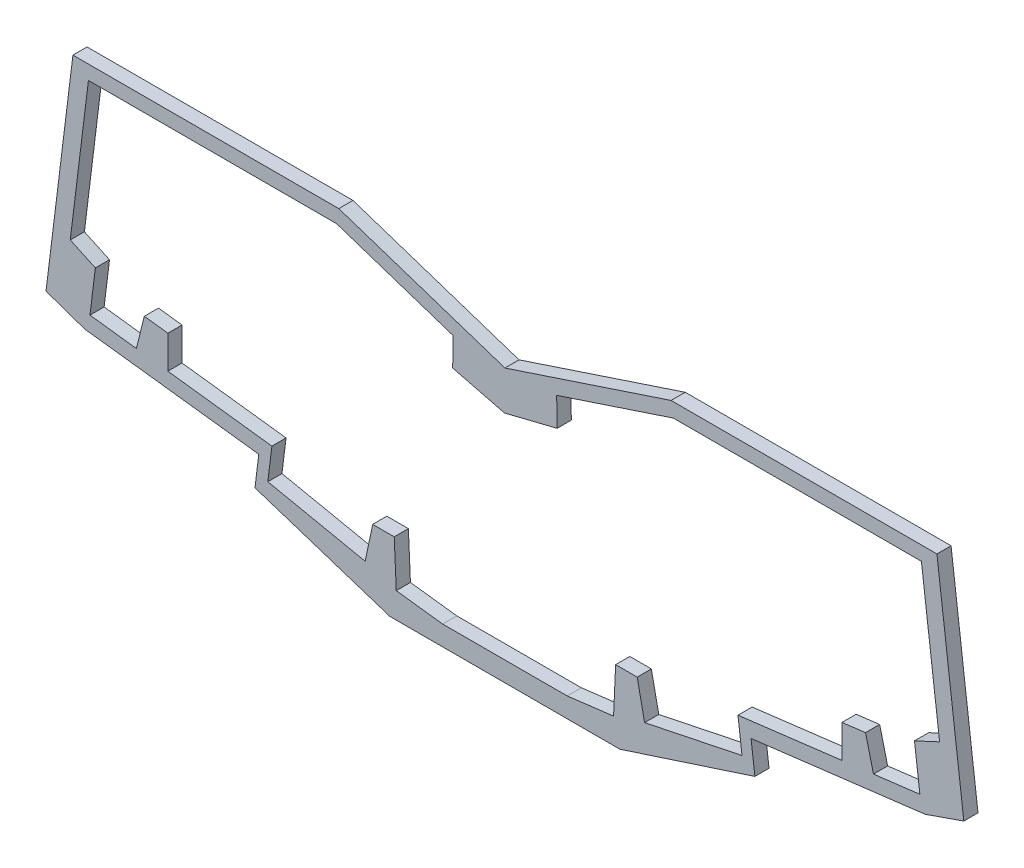
SolidWorks part; units mm, degrees
ref_plane "Спереди" through (0, 0, 0) normal (0, 0, 1) x (1, 0, 0)
ref_plane "Сверху" through (0, 0, 0) normal (0, 1, 0) x (1, 0, 0)
ref_plane "Справа" through (0, 0, 0) normal (1, 0, 0) x (0, 0, -1)
sketch "Контур" plane through (0, 0, 0) normal (0, 0, 1) x (1, 0, 0)
  line L0 (148.3547, -23.6716) -> (86.886, -31.2162)
  line L1 (162, -18.92) -> (148.3547, -23.6716)
  line L2 (-152.5, 58) -> (-58.64, 58)
  line L3 (86.886, -31.2162) -> (88.2371, -42.1562)
  line L4 (-10.9082, 11.6263) -> (-21.8482, 15.5133)
  line L5 (152.5, 58) -> (162, -18.92)
  line L6 (-88.2371, -42.1562) -> (-40.5971, -57.6623)
  line L7 (-58.64, 58) -> (0, 38.59)
  line L8 (-152.5, 58) -> (-162, -18.92)
  line L9 (58.64, 58) -> (0, 38.59)
  line L10 (-86.886, -31.2162) -> (-88.2371, -42.1562)
  line L11 (-40.5971, -57.6623) -> (40.5971, -57.6623)
  line L12 (-162, -18.92) -> (-148.3547, -23.6716)
  line L13 (0, 0) -> (0, -106.1018) construction
  line L14 (-148.3547, -23.6716) -> (-86.886, -31.2162)
  line L15 (88.2371, -42.1562) -> (40.5971, -57.6623)
  line L16 (152.5, 58) -> (58.64, 58)
  line L17 (-21.8482, 15.5133) -> (-18.6176, 3.8733)
  line L18 (21.8482, 15.5133) -> (18.6176, 3.8733)
  line L19 (10.9082, 11.6263) -> (21.8482, 15.5133)
  arc A0 (-18.6176, 3.8733) -> (18.6176, 3.8733) centre (0, -6.93) ccw
  arc A2 (10.9082, 11.6263) -> (-10.9082, 11.6263) centre (0, -6.93) ccw
  point P0 (0, 0)
  point P19 (0, -57.6623)
  dimension "D1" = 43.05
  dimension "D2" = 10.94
  dimension "D3" = 61.4687
  dimension "D6" = 47.64
  dimension "D7" = 50.1
  dimension "D8" = 11.64
  dimension "D9" = 12.08
  dimension "D10" = 11.61
  dimension "D11" = 45.52
sketch "Эскиз4" plane through (0, 0, 0) normal (0, 0, 1) x (1, 0, 0)
  line L0 (21.8482, 15.5133) -> (18.6176, 3.8733) construction
  line L1 (10.9082, 11.6263) -> (21.8482, 15.5133) construction
  line L2 (-10.9082, 11.6263) -> (-21.8482, 15.5133) construction
  line L3 (-21.8482, 15.5133) -> (-18.6176, 3.8733) construction
  line L4 (21.8482, 15.5133) -> (18.6176, 3.8733)
  line L5 (10.9082, 11.6263) -> (21.8482, 15.5133)
  line L6 (-10.9082, 11.6263) -> (-21.8482, 15.5133)
  line L7 (-21.8482, 15.5133) -> (-18.6176, 3.8733)
  line L12 (-21.8482, 15.5133) -> (-18.6176, 3.8733)
  line L13 (-21.8482, 15.5133) -> (-18.6176, 3.8733)
  line L14 (-10.9082, 11.6263) -> (-21.8482, 15.5133)
  line L15 (152.5, 58) -> (58.64, 58)
  line L16 (58.64, 58) -> (0, 38.59)
  line L17 (0, 38.59) -> (-58.64, 58)
  line L18 (-58.64, 58) -> (-152.5, 58)
  line L19 (-152.5, 58) -> (-162, -18.92)
  line L20 (-162, -18.92) -> (-148.3547, -23.6716)
  line L21 (-148.3547, -23.6716) -> (-86.886, -31.2162)
  line L22 (-86.886, -31.2162) -> (-88.2371, -42.1562)
  line L23 (-88.2371, -42.1562) -> (-40.5971, -57.6623)
  line L24 (-40.5971, -57.6623) -> (40.5971, -57.6623)
  line L25 (40.5971, -57.6623) -> (88.2371, -42.1562)
  line L26 (88.2371, -42.1562) -> (86.886, -31.2162)
  line L27 (86.886, -31.2162) -> (148.3547, -23.6716)
  line L28 (148.3547, -23.6716) -> (162, -18.92)
  line L29 (162, -18.92) -> (152.5, 58)
  line L30 (152.5, 58) -> (58.64, 58)
  line L31 (58.64, 58) -> (0, 38.59)
  line L32 (0, 38.59) -> (-58.64, 58)
  line L33 (-58.64, 58) -> (-152.5, 58)
  line L34 (-152.5, 58) -> (-162, -18.92)
  line L35 (-162, -18.92) -> (-148.3547, -23.6716)
  line L36 (-148.3547, -23.6716) -> (-86.886, -31.2162)
  line L37 (-86.886, -31.2162) -> (-88.2371, -42.1562)
  line L38 (-88.2371, -42.1562) -> (-40.5971, -57.6623)
  line L39 (-40.5971, -57.6623) -> (40.5971, -57.6623)
  line L40 (40.5971, -57.6623) -> (88.2371, -42.1562)
  line L41 (88.2371, -42.1562) -> (86.886, -31.2162)
  line L42 (86.886, -31.2162) -> (148.3547, -23.6716)
  line L43 (148.3547, -23.6716) -> (162, -18.92)
  line L44 (162, -18.92) -> (152.5, 58)
  line L45 (-10.9082, 11.6263) -> (-21.8482, 15.5133)
  line L46 (21.8482, 15.5133) -> (10.9082, 11.6263)
  line L47 (21.8482, 15.5133) -> (10.9082, 11.6263)
  line L48 (18.6176, 3.8733) -> (21.8482, 15.5133)
  line L49 (18.6176, 3.8733) -> (21.8482, 15.5133)
  arc A1 (-18.6176, 3.8733) -> (18.6176, 3.8733) centre (0, -6.93) ccw
  arc A2 (-18.6176, 3.8733) -> (18.6176, 3.8733) centre (0, -6.93) ccw
  arc A4 (10.9082, 11.6263) -> (-10.9082, 11.6263) centre (0, -6.93) ccw
  arc A5 (10.9082, 11.6263) -> (-10.9082, 11.6263) centre (0, -6.93) ccw
  dimension "D1" = 0
  dimension "D2" = 0
extrude "Бобышка-Вытянуть2" add sketch "Эскиз4" along normal blind 5 contours L43 L44 L30 L31 L32 L33 L34 L35 L36 L37 L38 L39 L40 L41 L42 A2 L5 L4 L7 L6
sketch "Эскиз5" plane through (0, 0, 5) normal (0, 0, 1) x (1, 0, 0)
sketch "Эскиз6" plane through (0, 0, 5) normal (0, 0, 1) x (1, 0, 0)
  line L0 (-144.5794, -3.0989) -> (-153.4415, 1.0185)
  line L1 (-146.014, 53) -> (-131.6233, 51.2227) construction
  line L2 (154.5624, -16.2154) -> (147.2152, -18.7739) construction
  line L3 (-146.014, 53) -> (-59.446, 53) construction
  line L4 (81.3104, -26.863) -> (82.7695, -38.6776) construction
  line L5 (-131.6233, 51.2227) -> (-127.6535, 50.7324) construction
  line L6 (-131.6233, 51.2227) -> (-94.9023, 46.6875) construction
  line L7 (-94.9023, 46.6875) -> (-90.5691, 49.139) construction
  line L8 (-90.5691, 49.139) -> (-76.1785, 47.3616) construction
  line L9 (-76.1785, 47.3616) -> (-71.7321, 50.6905) construction
  line L10 (-81.3104, -26.863) -> (-82.7695, -38.6776) construction
  line L11 (-71.7321, 50.6905) -> (-57.3415, 48.9132) construction
  line L12 (-57.3415, 48.9132) -> (-53.4669, 47.6512) construction
  line L13 (-53.4669, 47.6512) -> (-39.0763, 45.8739) construction
  line L14 (-39.0763, 45.8739) -> (-35.5206, 42.0298) construction
  line L15 (146.014, 53) -> (59.446, 53) construction
  line L17 (-86.886, -31.2162) -> (-88.2371, -42.1562) construction
  line L18 (-144.5794, -3.0989) -> (-146.4793, -18.482)
  line L19 (-146.4793, -18.482) -> (-130.1037, -20.5044)
  line L21 (-152.5, 58) -> (-58.64, 58) construction
  line L24 (86.886, -31.2162) -> (88.2371, -42.1562) construction
  line L27 (162, -18.92) -> (148.3547, -23.6716) construction
  line L28 (-35.5206, 42.0298) -> (-21.13, 40.2525) construction
  line L30 (-21.13, 40.2525) -> (-22.9073, 25.8618) construction
  line L149 (-118.9881, -21.8773) -> (-82.2624, -26.4131)
  line L150 (-82.2624, -26.4131) -> (-83.697, -38.0289)
  line L152 (76.1785, 47.3616) -> (90.5691, 49.139) construction
  line L271 (152.5, 58) -> (58.64, 58) construction
  line L272 (-130.1037, -20.5044) -> (-127.295, -9.2315)
  line L273 (-127.295, -9.2315) -> (-118.9881, -10.2575)
  line L274 (-118.9881, -10.2575) -> (-118.9881, -21.8773)
  line L275 (-83.697, -38.0289) -> (-49.3124, -45.1649)
  line L276 (-49.3124, -45.1649) -> (-46.6948, -32.5522)
  line L277 (-46.6948, -32.5522) -> (-39.0763, -32.5522)
  line L278 (-39.0763, -32.5522) -> (-38.357, -48.6499)
  line L279 (-38.357, -48.6499) -> (-21.9814, -50.6724)
  line L280 (-21.9814, -50.6724) -> (21.9814, -50.6724)
  line L281 (0, 0) -> (0, -106.1018) construction
  line L282 (-153.4415, 1.0185) -> (-147.0216, 53)
  line L283 (-147.0216, 53) -> (-59.446, 53)
  line L284 (-59.446, 53) -> (-18.2632, 39.3684)
  line L285 (-18.2632, 39.3684) -> (-18.4436, 29.37)
  line L286 (38.357, -48.6499) -> (21.9814, -50.6724)
  line L287 (39.0763, -32.5522) -> (38.357, -48.6499)
  line L288 (46.6948, -32.5522) -> (39.0763, -32.5522)
  line L289 (49.3124, -45.1649) -> (46.6948, -32.5522)
  line L290 (83.697, -38.0289) -> (49.3124, -45.1649)
  line L291 (82.2624, -26.4131) -> (83.697, -38.0289)
  line L292 (118.9881, -21.8773) -> (82.2624, -26.4131)
  line L293 (118.9881, -10.2575) -> (118.9881, -21.8773)
  line L294 (127.295, -9.2315) -> (118.9881, -10.2575)
  line L295 (130.1037, -20.5044) -> (127.295, -9.2315)
  line L296 (146.4793, -18.482) -> (130.1037, -20.5044)
  line L297 (144.5794, -3.0989) -> (146.4793, -18.482)
  line L298 (144.5794, -3.0989) -> (153.4415, 1.0185)
  line L299 (153.4415, 1.0185) -> (147.0216, 53)
  line L300 (147.0216, 53) -> (59.446, 53)
  line L301 (59.446, 53) -> (18.2632, 39.3684)
  line L302 (18.2632, 39.3684) -> (18.4436, 29.37)
  line L303 (-18.4436, 29.37) -> (-0.1973, 24.7509)
  line L304 (18.4436, 29.37) -> (-0.1973, 24.7509)
  line L305 (-22.9073, 25.8618) -> (-29.7101, -29.2197) construction
  line L306 (-29.7101, -29.2197) -> (-20.9706, -34.3295) construction
  line L307 (-20.9706, -34.3295) -> (-22.7479, -48.7201) construction
  line L308 (-22.7479, -48.7201) -> (-37.1385, -46.9428) construction
  line L309 (-37.1385, -46.9428) -> (-35.3612, -32.5522) construction
  line L310 (-35.3612, -32.5522) -> (-44.1008, -27.4424) construction
  line L311 (-44.1008, -27.4424) -> (-48.1467, -27.5681) construction
  line L312 (-48.1467, -27.5681) -> (-49.924, -41.9587) construction
  line L313 (-49.924, -41.9587) -> (-64.3147, -40.1814) construction
  line L314 (-64.3147, -40.1814) -> (-68.1892, -38.9195) construction
  line L315 (-68.1892, -38.9195) -> (-82.5799, -37.1422) construction
  line L316 (-82.5799, -37.1422) -> (-80.8026, -22.7515) construction
  line L317 (-80.8026, -22.7515) -> (-84.7586, -22.1105) construction
  line L318 (-84.7586, -22.1105) -> (-99.1493, -20.3332) construction
  line L319 (-99.1493, -20.3332) -> (-103.4825, -22.7847) construction
  line L320 (-103.4825, -22.7847) -> (-117.8731, -21.0074) construction
  line L321 (-117.8731, -21.0074) -> (-116.0958, -6.6167) construction
  line L322 (-116.0958, -6.6167) -> (-119.5753, -2.1566) construction
  line L323 (-119.5753, -2.1566) -> (-129.1963, -4.9988) construction
  line L324 (-129.1963, -4.9988) -> (-130.9736, -19.3894) construction
  line L325 (-130.9736, -19.3894) -> (-145.3642, -17.6121) construction
  line L326 (-145.3642, -17.6121) -> (-143.5869, -3.2214) construction
  line L327 (-143.5869, -3.2214) -> (-152.3265, 1.8883) construction
  line L328 (-152.3265, 1.8883) -> (-150.5492, 16.279) construction
  line L329 (-150.5492, 16.279) -> (-146.014, 53) construction
  line L330 (22.7479, -48.7201) -> (37.1385, -46.9428) construction
  line L331 (37.1385, -46.9428) -> (35.3612, -32.5522) construction
  line L332 (35.3612, -32.5522) -> (44.1008, -27.4424) construction
  line L333 (44.1008, -27.4424) -> (48.1467, -27.5681) construction
  line L334 (48.1467, -27.5681) -> (49.924, -41.9587) construction
  line L335 (49.924, -41.9587) -> (64.3147, -40.1814) construction
  line L336 (64.3147, -40.1814) -> (68.1892, -38.9195) construction
  line L337 (68.1892, -38.9195) -> (82.5799, -37.1422) construction
  line L338 (82.5799, -37.1422) -> (80.8026, -22.7515) construction
  line L339 (80.8026, -22.7515) -> (84.7586, -22.1105) construction
  line L340 (84.7586, -22.1105) -> (99.1493, -20.3332) construction
  line L341 (99.1493, -20.3332) -> (103.4825, -22.7847) construction
  line L342 (103.4825, -22.7847) -> (117.8731, -21.0074) construction
  line L343 (117.8731, -21.0074) -> (116.0958, -6.6167) construction
  line L344 (116.0958, -6.6167) -> (119.5753, -2.1566) construction
  line L345 (119.5753, -2.1566) -> (129.1963, -4.9988) construction
  line L346 (129.1963, -4.9988) -> (130.9736, -19.3894) construction
  line L347 (130.9736, -19.3894) -> (145.3642, -17.6121) construction
  line L348 (145.3642, -17.6121) -> (143.5869, -3.2214) construction
  line L349 (143.5869, -3.2214) -> (152.3265, 1.8883) construction
  line L350 (152.3265, 1.8883) -> (146.014, 53) construction
  line L351 (146.014, 53) -> (94.9023, 46.6875) construction
  line L352 (94.9023, 46.6875) -> (90.5691, 49.139) construction
  line L353 (76.1785, 47.3616) -> (71.7321, 50.6905) construction
  line L354 (71.7321, 50.6905) -> (57.3415, 48.9132) construction
  line L355 (57.3415, 48.9132) -> (53.4669, 47.6512) construction
  line L356 (53.4669, 47.6512) -> (39.0763, 45.8739) construction
  line L357 (39.0763, 45.8739) -> (35.5206, 42.0298) construction
  line L358 (35.5206, 42.0298) -> (21.13, 40.2525) construction
  line L359 (21.13, 40.2525) -> (29.7101, -29.2197) construction
  line L360 (29.7101, -29.2197) -> (20.9706, -34.3295) construction
  line L361 (20.9706, -34.3295) -> (22.7479, -48.7201) construction
  point P13 (0, -52.6623)
  point P301 (0, -50.6724)
  dimension "D2" = 5
  dimension "D6" = 5
  dimension "D10" = 5
  dimension "D12" = 5
  dimension "D14" = 5
  dimension "D15" = 5
  dimension "D84" = 3
  dimension "D85" = 3
  dimension "D86" = 10
  dimension "D87" = 10
other "Выровнять группу1"
other "Выровнять группу2"
extrude "Вырез-Вытянуть5" cut sketch "Эскиз6" against normal through all
